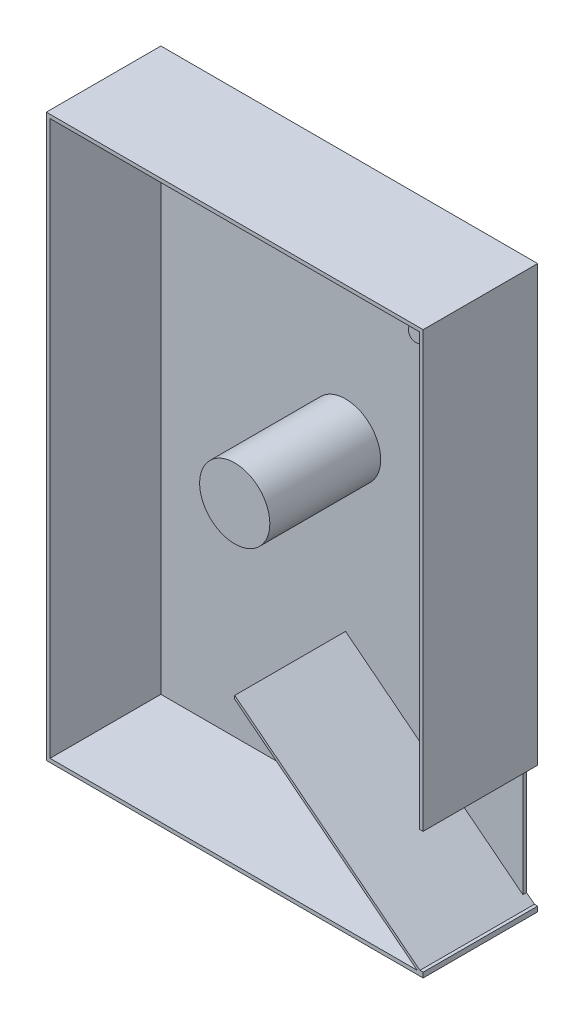
SolidWorks part; units mm, degrees
ref_plane "前视基准面" through (0, 0, 0) normal (0, 0, 1) x (1, 0, 0)
ref_plane "上视基准面" through (0, 0, 0) normal (0, 1, 0) x (1, 0, 0)
ref_plane "右视基准面" through (0, 0, 0) normal (1, 0, 0) x (0, 0, -1)
sketch "草图1" plane through (0, 0, 0) normal (0, 0, 1) x (1, 0, 0)
  line L1 (-50, -75) -> (50, -75)
  line L2 (-50, -75) -> (-50, 75)
  line L3 (-50, 75) -> (50, 75)
  line L4 (50, -75) -> (50, 75)
  line L5 (-50, -75) -> (50, 75) construction
  line L6 (-50, 75) -> (50, -75) construction
  line L7 (-51, 76) -> (51, 76)
  line L8 (-51, 76) -> (-51, -76)
  line L9 (-51, -76) -> (51, -76)
  line L10 (51, 76) -> (51, -76)
  line L11 (-51, 76) -> (51, -76) construction
  line L12 (-51, -76) -> (51, 76) construction
  point P0 (0, 0)
  point P6 (0, 0)
  dimension "D1" = 100
  dimension "D2" = 150
  dimension "D3" = 102
  dimension "D4" = 152
extrude "凸台-拉伸1" add sketch "草图1" along normal blind 30 contours L3 L4 L1 L2
sketch "草图2" plane through (0, 0, 0) normal (0, 1, 0) x (1, 0, 0)
  line L0 (-51, 0) -> (51, 0)
  line L1 (-51, -30) -> (-51, 0) construction
  line L2 (51, 0) -> (-51, 0) construction
  line L3 (51, 0) -> (51, 1)
  line L4 (51, 1) -> (-51, 1)
  line L5 (-51, 1) -> (-51, 0)
extrude "凸台-拉伸2" add sketch "草图2" along normal blind 76 and the other way blind 76
sketch "草图3" plane through (0, 0, 0) normal (0, 0, 1) x (1, 0, 0)
  circle A0 centre (0, 9.7646) radius 9.5
  dimension "D1" = 19
extrude "凸台-拉伸3" add sketch "草图3" along normal blind 30 contours A0
sketch "草图5" plane through (0, 0, 0) normal (0, 0, 1) x (1, 0, 0)
  line L1 (50, 75) -> (34, 75)
  line L2 (50, 75) -> (50, 59)
  line L3 (50, 59) -> (34, 59)
  line L4 (34, 75) -> (34, 59)
  circle A0 centre (34, 59) radius 2
  dimension "D1" = 16
  dimension "D2" = 16
extrude "凸台-拉伸4" add sketch "草图5" along normal blind 15 contours L4 A0 L3 | L3 A0 L4
sketch "草图6" plane through (51, 0, 0) normal (1, 0, 0) x (0, 0, -1)
  line L0 (-30, -76) -> (-30, 76) construction
  line L1 (-30, -74.6402) -> (1, -74.6402)
  line L2 (-30, -74.6402) -> (-30, -41.6223)
  line L3 (-30, -41.6223) -> (1, -41.6223)
  line L4 (1, -74.6402) -> (1, -41.6223)
  line L5 (1, -76) -> (1, 76) construction
extrude "切除-拉伸1" cut sketch "草图6" against normal blind 3
sketch "草图7" plane through (0, 0, 30) normal (0, 0, 1) x (1, 0, 0)
  line L0 (51, -75.3201) -> (0, -35.2354)
  line L1 (51, -76) -> (51, -74.6402) construction
  line L2 (0, -35.2354) -> (0, -76)
  line L3 (-51, -76) -> (51, -76) construction
  line L4 (0, -76) -> (51, -75.3201)
  line L5 (0, -75) -> (51, -75.3201)
  line L6 (-50, -75) -> (50, -75) construction
  line L7 (-1.4474, -35.013) -> (-1.4474, -74.9909)
  line L8 (-1.4474, -35.013) -> (49.8262, -75.3128)
  circle A0 centre (0, 9.7646) radius 45
  point P15 (49.8265, -75.3358)
  point P17 (0.9245, -32.1938)
  point P18 (0.8064, -32.2999)
extrude "凸台-拉伸5" add sketch "草图7" against normal blind 31 contours L7 L8 L5 L0 L2
